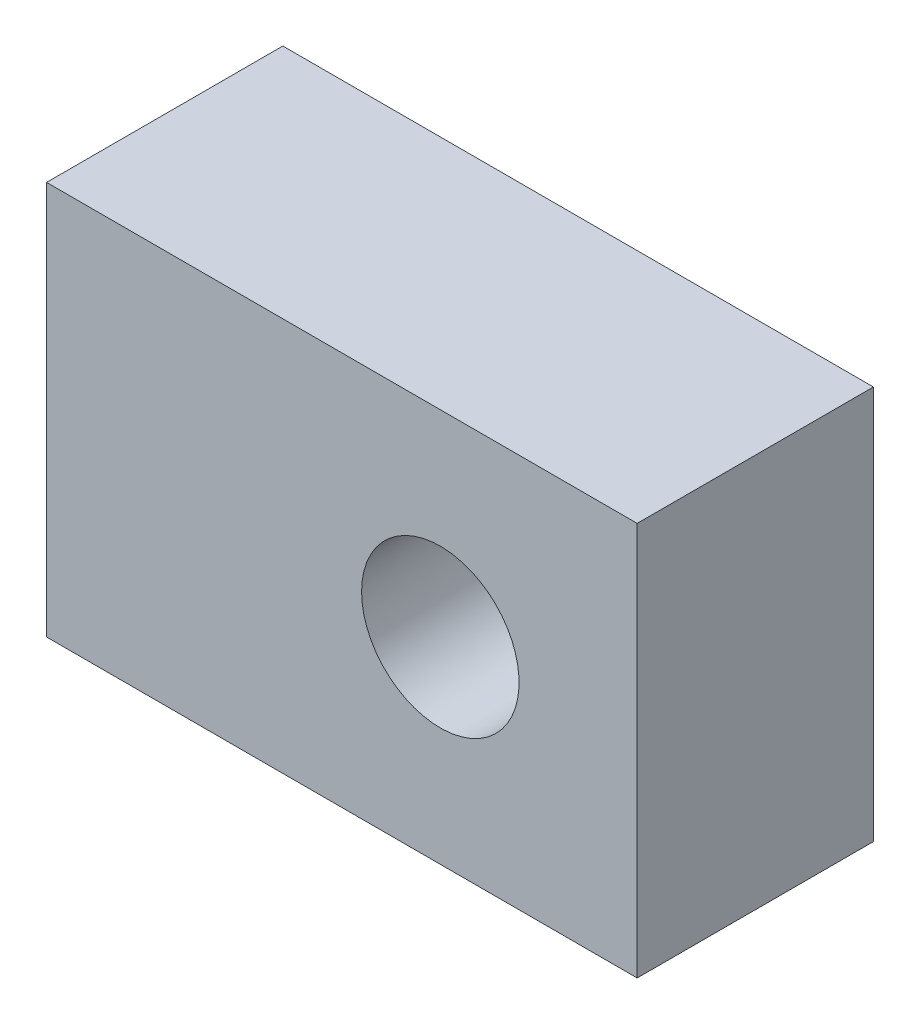
SolidWorks part; units mm, degrees
ref_plane "Front Plane" through (0, 0, 0) normal (0, 0, 1) x (1, 0, 0)
ref_plane "Top Plane" through (0, 0, 0) normal (0, 1, 0) x (1, 0, 0)
ref_plane "Right Plane" through (0, 0, 0) normal (1, 0, 0) x (0, 0, -1)
sketch "Sketch1" plane through (0, 0, 0) normal (0, 0, 1) x (1, 0, 0)
  line L1 (0, 0) -> (15, 0)
  line L2 (0, 0) -> (0, 10)
  line L3 (0, 10) -> (15, 10)
  line L4 (15, 0) -> (15, 10)
  dimension "D1" = 10
  dimension "D2" = 15
extrude "Boss-Extrude1" add sketch "Sketch1" along normal blind 6
sketch "Sketch2" plane through (0, 0, 0) normal (0, 0, -1) x (-1, 0, 0)
  line L0 (-15, 10) -> (0, 10) construction
  line L2 (-15, 0) -> (-15, 10) construction
  circle A0 centre (-10, 5) radius 2
  dimension "D1" = 2
  dimension "D2" = 5
  dimension "D3" = 5
extrude "Cut-Extrude1" cut sketch "Sketch2" against normal blind 6
